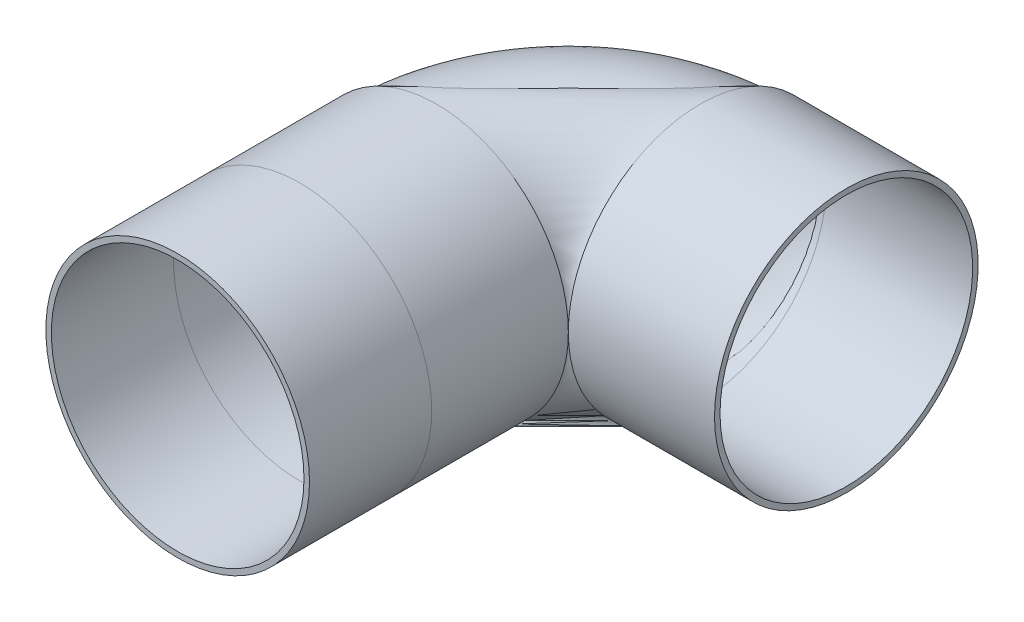
SolidWorks part; units mm, degrees
ref_plane "Спереди" through (0, 0, 0) normal (0, 0, 1) x (1, 0, 0)
ref_plane "Сверху" through (0, 0, 0) normal (0, 1, 0) x (1, 0, 0)
ref_plane "Справа" through (0, 0, 0) normal (1, 0, 0) x (0, 0, -1)
sketch "Эскиз1" plane through (0, 0, 0) normal (0, 1, 0) x (1, 0, 0)
  line L0 (0, -57) -> (0, 0)
  line L1 (55, 55) -> (116, 55)
  line L2 (0, -57) -> (0, -108)
  arc A0 (0, 0) -> (55, 55) centre (55, 0) cw
  dimension "D1" = 55
  dimension "D4" = 61
  dimension "D2" = 57
  dimension "D3" = 51
ref_plane "Плоскость4" through (0, 0, 108) normal (0, 0, 1) x (1, 0, 0)
sketch "Эскиз3" plane through (0, 0, 108) normal (0, 0, 1) x (1, 0, 0)
  circle A0 centre (0, 0) radius 55
  circle A1 centre (0, 0) radius 52.7
  dimension "D1" = 110
  dimension "D2" = 105.4
sweep "По траектории1" add profiles "Эскиз3" path "Эскиз1"
